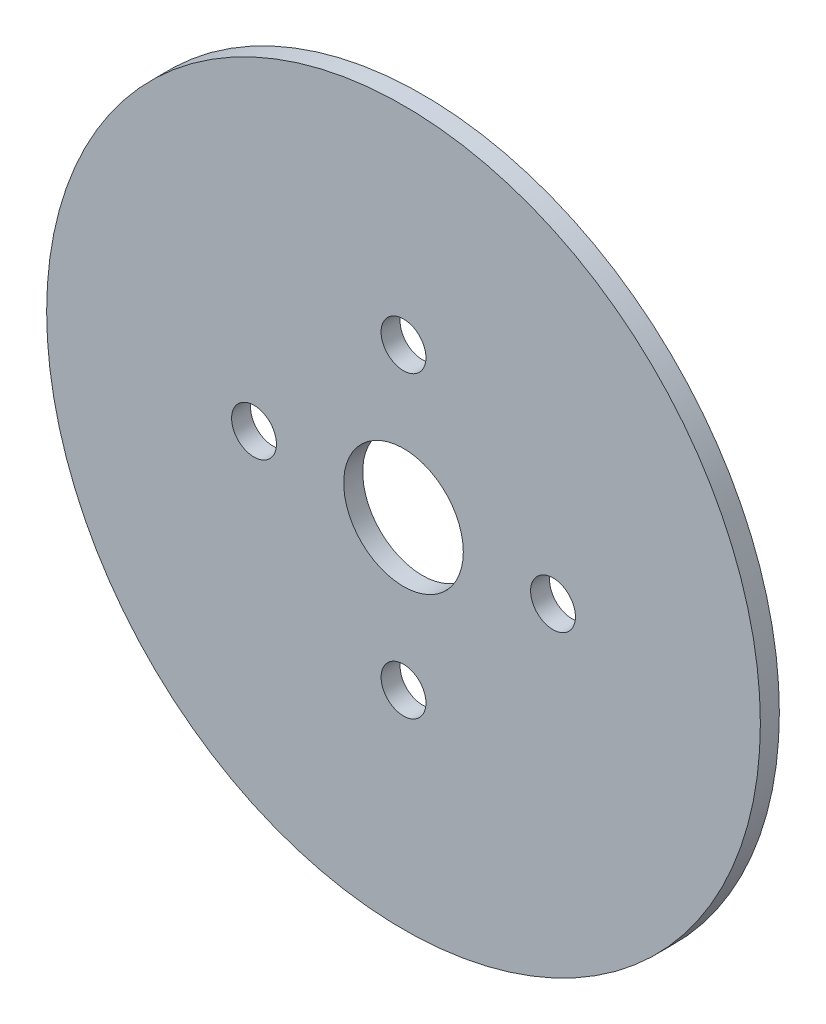
SolidWorks part; units mm, degrees
ref_plane "Front Plane" through (0, 0, 0) normal (0, 0, 1) x (1, 0, 0)
ref_plane "Top Plane" through (0, 0, 0) normal (0, 1, 0) x (1, 0, 0)
ref_plane "Right Plane" through (0, 0, 0) normal (1, 0, 0) x (0, 0, -1)
sketch "Sketch1" plane through (0, 0, 0) normal (0, 0, 1) x (1, 0, 0)
  circle A0 centre (0, 10) radius 1.5
  circle A1 centre (0, 0) radius 23.87
  circle A6 centre (0, 0) radius 4
  circle A7 centre (10, 0) radius 1.5
  circle A8 centre (0, -10) radius 1.5
  circle A9 centre (-10, 0) radius 1.5
  dimension "D1" = 4
extrude "Boss-Extrude2" add sketch "Sketch1" along normal blind 1.27
